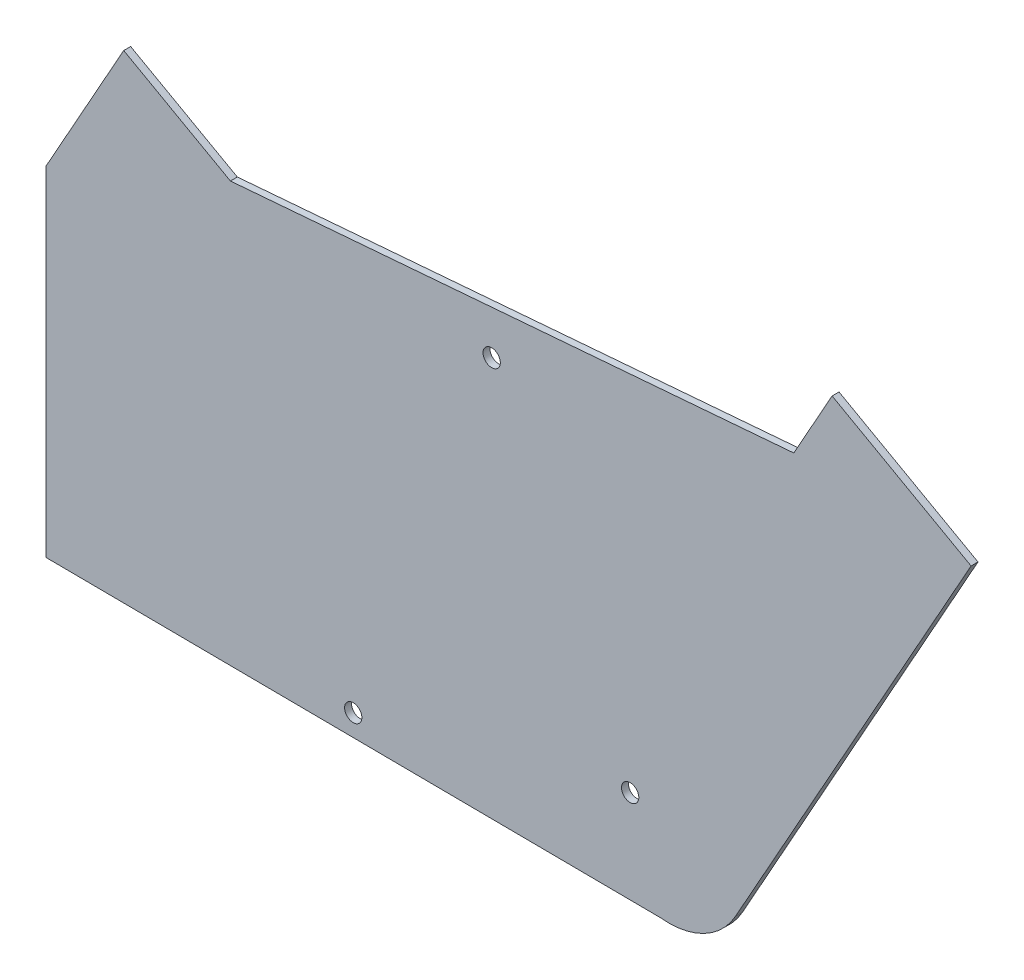
SolidWorks part; units mm, degrees
ref_plane "Front Plane" through (0, 0, 0) normal (0, 0, 1) x (1, 0, 0)
ref_plane "Top Plane" through (0, 0, 0) normal (0, 1, 0) x (1, 0, 0)
ref_plane "Right Plane" through (0, 0, 0) normal (1, 0, 0) x (0, 0, -1)
sketch "Sketch1" plane through (0, 0, 0) normal (0, 0, 1) x (1, 0, 0)
  line L0 (56.4756, 100.9656) -> (70.5416, 126.1124)
  line L1 (70.5416, 126.1124) -> (121.5274, 97.5933)
  line L2 (121.5274, 97.5933) -> (35.0363, -57.0334)
  line L4 (-217.8877, 54.9384) -> (-189.3686, 105.9242)
  line L5 (-189.3686, 105.9242) -> (-150.227, 84.0302)
  line L6 (-150.227, 84.0302) -> (56.4756, 100.9656)
  line L7 (-217.8877, 54.9384) -> (-217.8877, -69.4209)
  line L8 (-217.8877, -69.4209) -> (7.6107, -71.1678)
  arc A0 (35.0363, -57.0334) -> (7.6107, -71.1678) centre (10.6517, -43.3938) cw
  point P8 (11.9214, -69.0626)
  point P11 (0, 0)
  dimension "D3" = 27.94
  dimension "D1" = 58.42
  dimension "D2" = 58.42
extrude "Boss-Extrude1" add sketch "Sketch1" along normal blind 2.54
sketch "Sketch2" plane through (0, 0, 2.54) normal (0, 0, 1) x (1, 0, 0)
  line L0 (-3.5626, 96.0466) -> (-3.5626, -67.4478)
  line L1 (56.4756, 100.9656) -> (-150.227, 84.0302) construction
  arc A2 (7.6107, -71.1678) -> (35.0363, -57.0334) centre (10.6517, -43.3938) ccw construction
  circle A3 centre (-3.5626, -36.9678) radius 3.175
  circle A4 centre (-54.3626, 75.8082) radius 3.175
  circle A5 centre (-105.1626, -62.3678) radius 3.175
  dimension "D1" = 6.35
  dimension "D3" = 6.35
  dimension "D6" = 6.35
  dimension "D2" = 30.48
  dimension "D4" = 50.8
  dimension "D5" = 112.776
  dimension "D7" = 101.6
  dimension "D8" = 25.4
extrude "Cut-Extrude1" cut sketch "Sketch2" against normal through all contours L0 A3 | L0 A3 | A4 | A5
